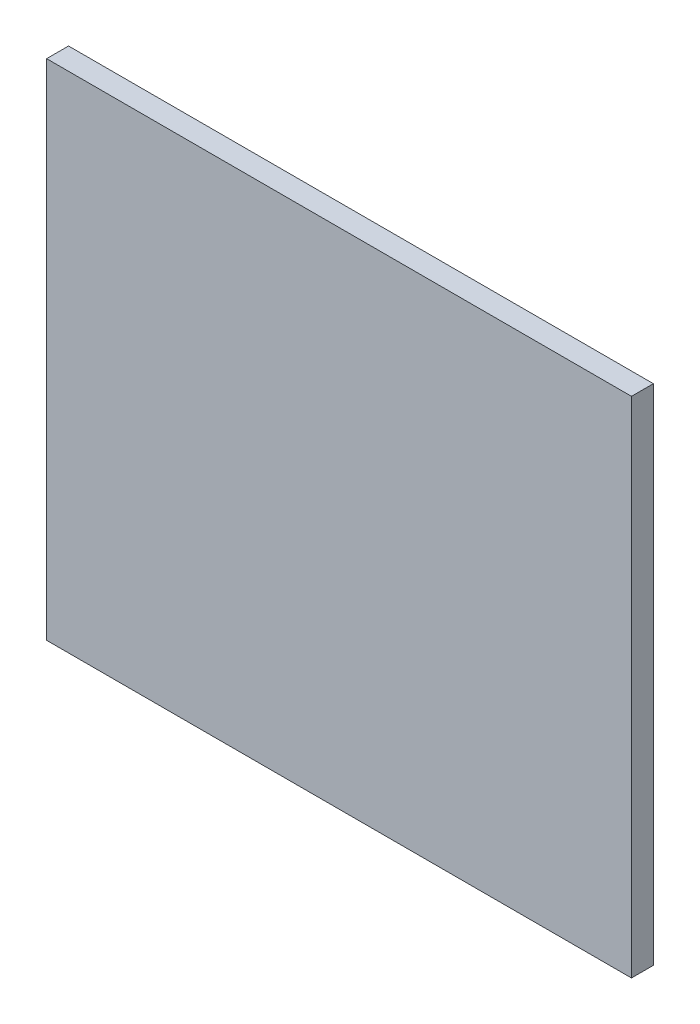
SolidWorks part; units mm, degrees
ref_plane "Alzado" through (0, 0, 0) normal (0, 0, 1) x (1, 0, 0)
ref_plane "Planta" through (0, 0, 0) normal (0, 1, 0) x (1, 0, 0)
ref_plane "Vista lateral" through (0, 0, 0) normal (1, 0, 0) x (0, 0, -1)
sketch "Croquis1" plane through (0, 0, 0) normal (0, 0, 1) x (1, 0, 0)
  line L0 (169.5, 146) -> (-169.5, -146) construction
  line L1 (-169.5, 146) -> (169.5, 146)
  line L2 (-169.5, 146) -> (-169.5, -146)
  line L3 (-169.5, -146) -> (169.5, -146)
  line L4 (169.5, 146) -> (169.5, -146)
  line L5 (-169.5, -146) -> (-169.5, -147.0724) construction
  dimension "D1" = 292
  dimension "D2" = 339
extrude "Saliente-Extruir1" add sketch "Croquis1" along normal blind 12.7
